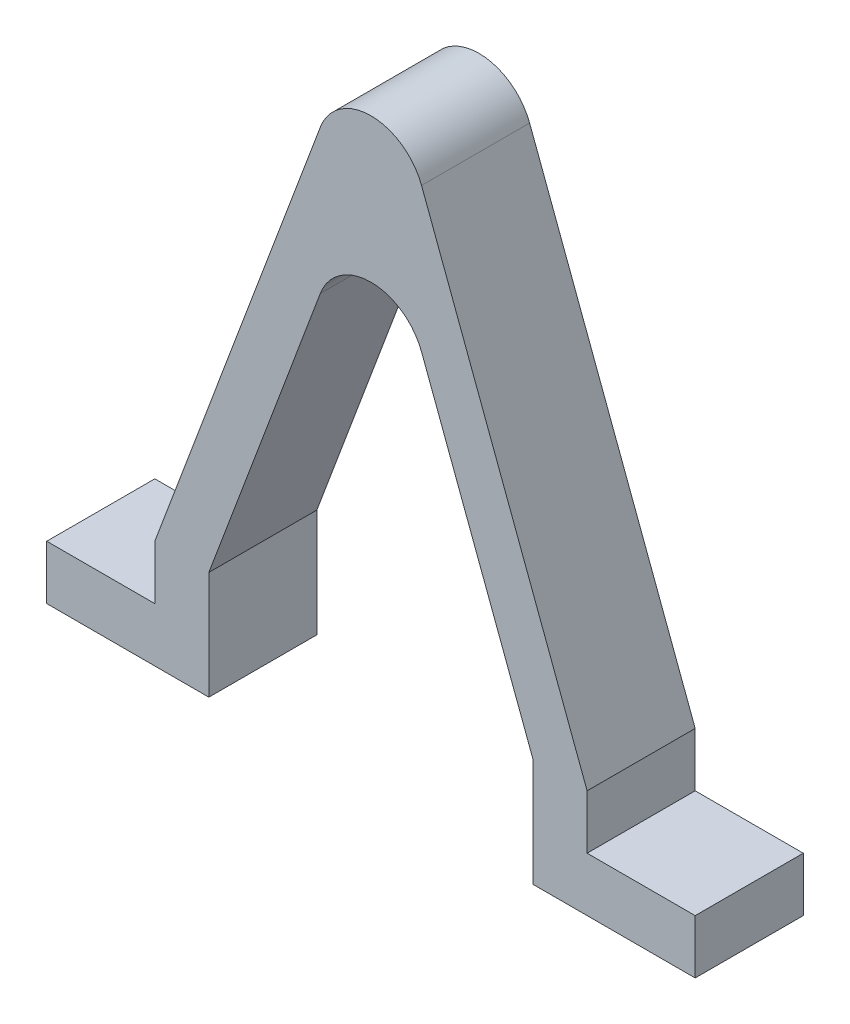
SolidWorks part; units mm, degrees
ref_plane "Front Plane" through (0, 0, 0) normal (0, 0, 1) x (1, 0, 0)
ref_plane "Top Plane" through (0, 0, 0) normal (0, 1, 0) x (1, 0, 0)
ref_plane "Right Plane" through (0, 0, 0) normal (1, 0, 0) x (0, 0, -1)
sketch "Sketch1" plane through (0, 0, 0) normal (0, 0, 1) x (1, 0, 0)
  line L0 (0, 0) -> (15, 0)
  line L3 (45, 0) -> (60, 0)
  line L4 (60, 0) -> (60, 5)
  line L5 (60, 5) -> (50, 5)
  line L6 (50, 5) -> (50, 10)
  line L7 (50, 10) -> (30, 63.3333)
  line L8 (30, 63.3333) -> (10, 10)
  line L9 (10, 10) -> (10, 5)
  line L10 (10, 5) -> (0, 5)
  line L11 (0, 5) -> (0, 0)
  line L12 (15, 0) -> (15, 10)
  line L13 (15, 10) -> (30, 50)
  line L14 (30, 50) -> (45, 10)
  line L15 (45, 10) -> (45, 0)
  point P4 (45, 9.1484)
  point P13 (0, 0)
  point P16 (27.9524, 36.8279)
  point P17 (26.4355, 37.1037)
  point P18 (29.0557, 40.6891)
  point P19 (0, 0)
  point P20 (27.1536, 68.4946)
  point P21 (0, 0)
  point P22 (30, 65.3047)
  dimension "D1" = 5
  dimension "D2" = 30
  dimension "D3" = 15
  dimension "D4" = 15
  dimension "D5" = 10
  dimension "D6" = 10
  dimension "D7" = 5
  dimension "D8" = 50
extrude "Boss-Extrude1" add sketch "Sketch1" along normal blind 10
fillet "Fillet1" radius 5 1 edges at (30, 50, 5)
fillet "Fillet2" radius 5 1 edges at (30, 63.3333, 5)
